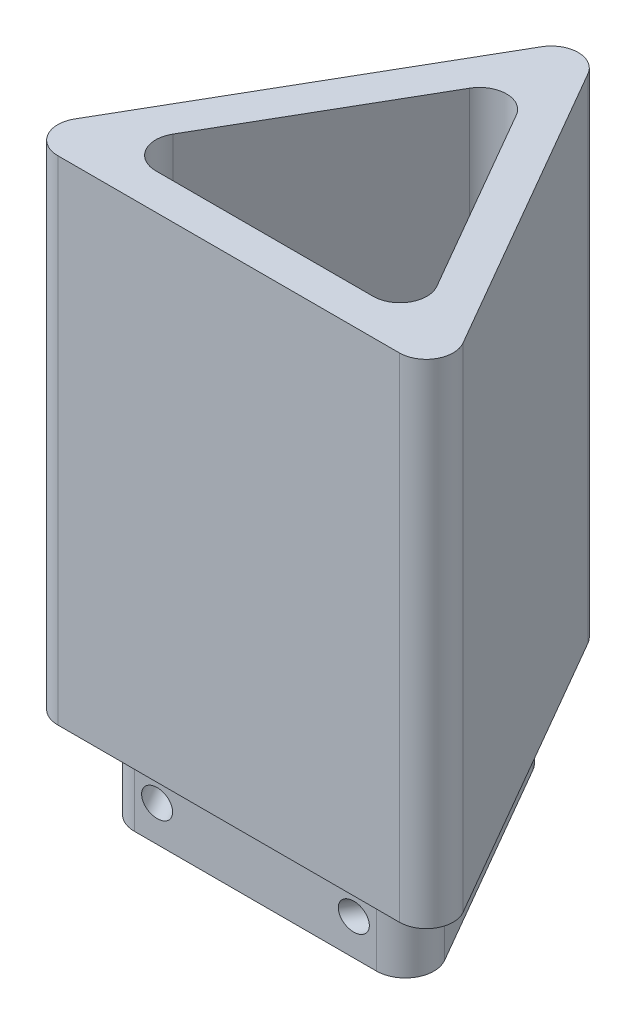
SolidWorks part; units mm, degrees
ref_plane "前视基准面" through (0, 0, 0) normal (0, 0, 1) x (1, 0, 0)
ref_plane "上视基准面" through (0, 0, 0) normal (0, 1, 0) x (1, 0, 0)
ref_plane "右视基准面" through (0, 0, 0) normal (1, 0, 0) x (0, 0, -1)
other "Configuration Table"
sketch "草图1" plane through (0, 0, 0) normal (0, 1, 0) x (1, 0, 0)
  line L0 (0, 0) -> (0, 35.0266) construction
  line L1 (0, 22) -> (-19.0526, -11)
  line L2 (-19.0526, -11) -> (19.0526, -11)
  line L3 (19.0526, -11) -> (0, 22)
  line L4 (0, 12) -> (-10.3923, -6)
  line L5 (-10.3923, -6) -> (10.3923, -6)
  line L6 (10.3923, -6) -> (0, 12)
  circle A0 centre (0, 0) radius 11 construction
  dimension "D1" = 33
  dimension "D2" = 5
extrude "凸台-拉伸1" add sketch "草图1" along normal blind 9
sketch "草图3" plane through (0, 9, 0) normal (0, 1, 0) x (1, 0, 0)
  line L0 (0, 0) -> (0, 37.3625) construction
  line L2 (0, 28) -> (-24.2487, -14)
  line L3 (-24.2487, -14) -> (24.2487, -14)
  line L4 (24.2487, -14) -> (0, 28)
  line L5 (0, 12) -> (-10.3923, -6)
  line L6 (-10.3923, -6) -> (10.3923, -6)
  line L7 (10.3923, -6) -> (0, 12)
  circle A0 centre (0, 0) radius 14 construction
  circle A1 centre (0, 0) radius 6 construction
  dimension "D1" = 42
extrude "凸台-拉伸2" add sketch "草图3" along normal blind 5
fillet "圆角1" radius 3.2 3 edges at (0, 4.5, -22) (19.0526, 4.5, 11) (-19.0526, 4.5, 11)
sketch "草图5" plane through (7, -46, 0) normal (1, 0, 0) x (0, 0, -1)
  circle A0 centre (15, 50) radius 1.5
  dimension "D1" = 3
extrude "切除-拉伸1" cut sketch "草图5" against normal blind 18
pattern_circular "阵列(圆周)1" count 3 over 360 of "切除-拉伸1"
fillet "圆角2" radius 3 3 edges at (-24.2487, 11.5, 14) (0, 11.5, -28) (24.2487, 11.5, 14)
sketch "草图6" plane through (0, 14, 0) normal (0, 1, 0) x (1, 0, 0)
  line L0 (0, 20) -> (-17.3205, -10)
  line L1 (-17.3205, -10) -> (17.3205, -10)
  line L2 (17.3205, -10) -> (0, 20)
  line L3 (-2.5981, 23.5) -> (-21.6506, -9.5)
  line L4 (-19.0526, -14) -> (19.0526, -14)
  line L5 (21.6506, -9.5) -> (2.5981, 23.5)
  line L6 (-2.5981, 23.5) -> (-21.6506, -9.5)
  line L7 (-19.0526, -14) -> (19.0526, -14)
  line L8 (21.6506, -9.5) -> (2.5981, 23.5)
  arc A0 (-17.3205, -10) -> (-17.3205, -10) centre (-17.3205, -10) ccw
  arc A1 (17.3205, -10) -> (17.3205, -10) centre (17.3205, -10) ccw
  arc A2 (0, 20) -> (0, 20) centre (0, 20) ccw
  arc A3 (-21.6506, -9.5) -> (-19.0526, -14) centre (-19.0526, -11) ccw
  arc A4 (19.0526, -14) -> (21.6506, -9.5) centre (19.0526, -11) ccw
  arc A5 (2.5981, 23.5) -> (-2.5981, 23.5) centre (0, 22) ccw
  arc A6 (-21.6506, -9.5) -> (-19.0526, -14) centre (-19.0526, -11) ccw
  arc A7 (19.0526, -14) -> (21.6506, -9.5) centre (19.0526, -11) ccw
  arc A8 (2.5981, 23.5) -> (-2.5981, 23.5) centre (0, 22) ccw
  dimension "D1" = 0
  dimension "D2" = 4
extrude "凸台-拉伸3" add sketch "草图6" along normal blind 50
fillet "圆角3" radius 3 6 edges at (17.3205, 39, 10) (-17.3205, 39, 10) (0, 39, -20) (-8.6603, 14, -5) (8.6603, 14, -5) (0, 14, 10)
